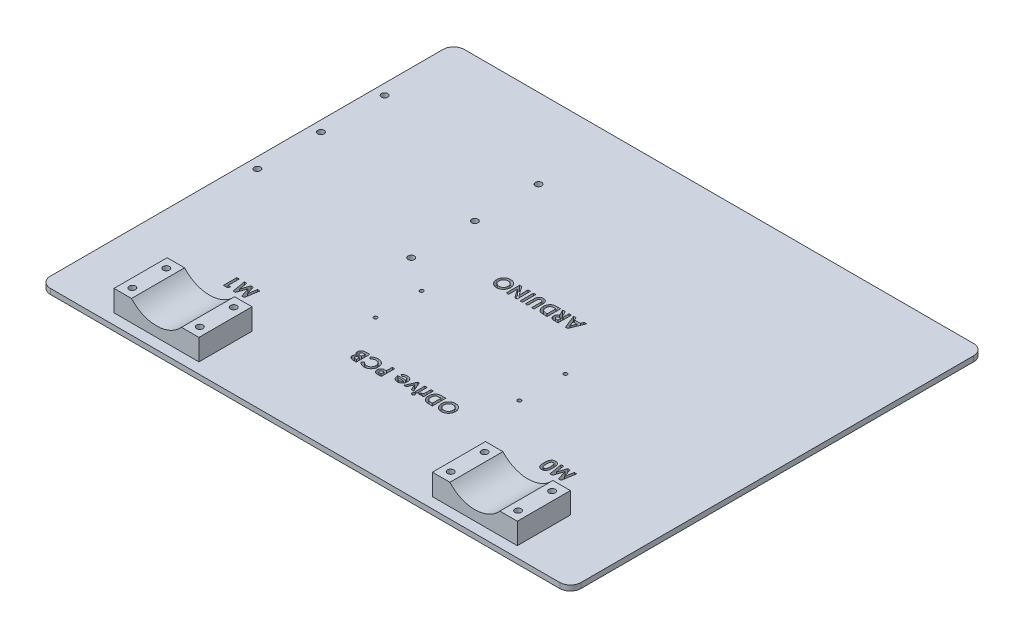
SolidWorks part; units mm, degrees
ref_plane "Plan de face" through (0, 0, 0) normal (0, 0, 1) x (1, 0, 0)
ref_plane "Plan de dessus" through (0, 0, 0) normal (0, 1, 0) x (1, 0, 0)
ref_plane "Plan de droite" through (0, 0, 0) normal (1, 0, 0) x (0, 0, -1)
sketch "Esquisse1" plane through (0, 0, 0) normal (0, 1, 0) x (1, 0, 0)
  line L1 (240, -150) -> (-240, -150)
  line L2 (250, -140) -> (250, 140)
  line L3 (240, 150) -> (-240, 150)
  line L4 (-250, -140) -> (-250, 140)
  line L5 (250, -150) -> (-250, 150) construction
  line L6 (250, 150) -> (-250, -150) construction
  arc A0 (-240, -150) -> (-250, -140) centre (-240, -140) cw
  arc A1 (240, -150) -> (250, -140) centre (240, -140) ccw
  arc A2 (250, 140) -> (240, 150) centre (240, 140) ccw
  arc A3 (-240, 150) -> (-250, 140) centre (-240, 140) ccw
  point P0 (0, 0)
  dimension "D3" = 10
  dimension "D1" = 300
  dimension "D2" = 500
extrude "Boss.-Extru.1" add sketch "Esquisse1" along normal blind 5
sketch "Esquisse2" plane through (0, 5, 0) normal (0, 1, 0) x (1, 0, 0)
  line L0 (240, 150) -> (-240, 150) construction
  line L1 (-240, -150) -> (240, -150) construction
  line L2 (250, -140) -> (250, 140) construction
  line L3 (-250, 140) -> (-250, -140) construction
  spline S4 degree 3 poles (74.2, -20.6163) (74.2, -17.2163) (70.8, -17.2163) (70.8, -20.6163) (70.8, -24.0163) (74.2, -24.0163) (74.2, -20.6163) (74.2, -17.2163) (70.8, -17.2163) knots -0.5 0 0 0 0.5 0.5 0.5 1 1 1 1.5 1.5 1.5 weights 1 0.333333 0.333333 1 0.333333 0.333333 1 0.333333 0.333333 only from (74.2, -20.6163) to (74.2, -20.6163)
  spline S5 degree 3 poles (74.2, 22.8837) (74.2, 26.2837) (70.8, 26.2837) (70.8, 22.8837) (70.8, 19.4837) (74.2, 19.4837) (74.2, 22.8837) (74.2, 26.2837) (70.8, 26.2837) knots -0.5 0 0 0 0.5 0.5 0.5 1 1 1 1.5 1.5 1.5 weights 1 0.333333 0.333333 1 0.333333 0.333333 1 0.333333 0.333333 only from (74.2, 22.8837) to (74.2, 22.8837)
  spline S6 degree 3 poles (-61.3, -20.6162) (-61.3, -17.2162) (-64.7, -17.2162) (-64.7, -20.6162) (-64.7, -24.0162) (-61.3, -24.0162) (-61.3, -20.6162) (-61.3, -17.2162) (-64.7, -17.2162) knots -0.5 0 0 0 0.5 0.5 0.5 1 1 1 1.5 1.5 1.5 weights 1 0.333333 0.333333 1 0.333333 0.333333 1 0.333333 0.333333 only from (-61.3, -20.6162) to (-61.3, -20.6162)
  spline S7 degree 3 poles (-61.3, 22.8838) (-61.3, 26.2837) (-64.7, 26.2838) (-64.7, 22.8838) (-64.7, 19.4838) (-61.3, 19.4838) (-61.3, 22.8838) (-61.3, 26.2837) (-64.7, 26.2838) knots -0.5 0 0 0 0.5 0.5 0.5 1 1 1 1.5 1.5 1.5 weights 1 0.333333 0.333333 1 0.333333 0.333333 1 0.333333 0.333333 only from (-61.3, 22.8838) to (-61.3, 22.8838)
  dimension "D1" = 127.1162
  dimension "D2" = 127.1163
  dimension "D3" = 129.3837
  dimension "D4" = 129.3838
  dimension "D5" = 135.5
  dimension "D6" = 175.8
  dimension "D7" = 175.8
  dimension "D8" = 188.7
extrude "Enlèv. mat.-Extru.1" cut sketch "Esquisse2" against normal through all contours S7 | S6 | S5 | S4
sketch "Esquisse3" plane through (0, 0, 150) normal (0, 0, 1) x (1, 0, 0)
  line L0 (-240, 5) -> (240, 5) construction
  line L1 (-190, 5) -> (-110, 5)
  line L2 (-190, 5) -> (-190, 25)
  line L3 (-190, 25) -> (-173.5557, 25)
  line L4 (-110, 5) -> (-110, 25)
  line L5 (-240, 5) -> (-240, 0) construction
  line L6 (-150, -5.8486) -> (-150, 68.1347) construction
  line L7 (-126.4443, 25) -> (-110, 25)
  arc A0 (-173.5557, 25) -> (-126.4443, 25) centre (-150, 45.9136) ccw
  dimension "D4" = 63
  dimension "D1" = 80
  dimension "D2" = 20
  dimension "D3" = 50
  dimension "D5" = 20.9136
  dimension "D6" = 16.4443
extrude "Boss.-Extru.2" add sketch "Esquisse3" along normal blind 50 from offset 60 offset against normal yes
sketch "Esquisse4" plane through (0, 25, 0) normal (0, 1, 0) x (1, 0, 0)
  line L0 (-181.7778, -90) -> (-181.7778, -143.1865) construction
  line L1 (-173.5557, -90) -> (-190, -90) construction
  line L2 (-150, -90) -> (-150, -156.1953) construction
  line L3 (-190, -90) -> (-110, -90) construction
  line L4 (-173.5557, -140) -> (-190, -140) construction
  circle A0 centre (-181.7778, -99) radius 3
  circle A1 centre (-181.7778, -131) radius 3
  circle A2 centre (-118.2222, -131) radius 3
  circle A3 centre (-118.2222, -99) radius 3
  dimension "D1" = 6
  dimension "D2" = 6
  dimension "D4" = 9
  dimension "D3" = 9
extrude "Enlèv. mat.-Extru.2" cut sketch "Esquisse4" against normal through all
mirror "Symétrie1" about plane through (0, 0, 0) normal (1, 0, 0) of "Enlèv. mat.-Extru.2", "Boss.-Extru.2"
sketch "Esquisse5" plane through (0, 5, 0) normal (0, 1, 0) x (1, 0, 0)
  line L0 (250, -140) -> (250, 140) construction
  line L1 (-250, 140) -> (250, 140)
  line L2 (-250, 140) -> (-250, 240)
  line L3 (-250, 240) -> (250, 240)
  line L4 (250, 140) -> (250, 240)
  dimension "D1" = 100
extrude "Boss.-Extru.3" add sketch "Esquisse5" against normal up to surface (5 mm away) up to face at (118.2222, 0, 96)
fillet "Congé1" radius 10 2 edges at (-250, 2.5, -240) (250, 2.5, -240)
sketch "Esquisse6" plane through (0, 5, 0) normal (0, 1, 0) x (1, 0, 0)
  line L0 (-240, 256.0019) -> (-240, 35.9163) construction
  line L1 (-250, 230) -> (-250, -140) construction
  line L2 (240, 240) -> (-240, 240) construction
  circle A0 centre (-240, 165) radius 3
  circle A1 centre (-240, 105) radius 3
  circle A2 centre (-240, 45) radius 3
  circle A6 centre (-95, 165) radius 3
  circle A7 centre (-95, 105) radius 3
  circle A8 centre (-95, 45) radius 3
  dimension "D2" = 6
  dimension "D1" = 10
  dimension "D4" = 75
  dimension "D3" = 3
  dimension "D5" = 2
extrude "Enlèv. mat.-Extru.3" cut sketch "Esquisse6" against normal through all
sketch "Esquisse7" plane through (0, 0, 0) normal (0, -1, 0) x (1, 0, 0)
  line L0 (-250, -230) -> (-250, 140) construction
  line L1 (-237.5, 130) -> (-222.5, 130)
  line L2 (-237.5, 130) -> (-237.5, 115)
  line L3 (-237.5, 115) -> (-222.5, 115)
  line L4 (-222.5, 130) -> (-222.5, 115)
  line L5 (-237.5, 130) -> (-222.5, 115) construction
  line L6 (-237.5, 115) -> (-222.5, 130) construction
  line L7 (-240, 150) -> (240, 150) construction
  line L8 (0, 249.5345) -> (0, -298.3398) construction
  line L10 (-237.5, -212.5) -> (-222.5, -212.5)
  line L11 (-237.5, -212.5) -> (-237.5, -227.5)
  line L12 (-237.5, -227.5) -> (-222.5, -227.5)
  line L13 (-222.5, -212.5) -> (-222.5, -227.5)
  line L14 (-237.5, -212.5) -> (-222.5, -227.5) construction
  line L15 (-237.5, -227.5) -> (-222.5, -212.5) construction
  line L16 (240, -240) -> (-240, -240) construction
  line L17 (237.5, -227.5) -> (222.5, -212.5) construction
  line L18 (237.5, -212.5) -> (222.5, -227.5) construction
  line L19 (237.5, 115) -> (222.5, 130) construction
  line L20 (237.5, 130) -> (222.5, 115) construction
  line L21 (222.5, -212.5) -> (222.5, -227.5)
  line L22 (237.5, -227.5) -> (222.5, -227.5)
  line L23 (237.5, -212.5) -> (237.5, -227.5)
  line L24 (237.5, -212.5) -> (222.5, -212.5)
  line L25 (222.5, 130) -> (222.5, 115)
  line L26 (237.5, 115) -> (222.5, 115)
  line L27 (237.5, 130) -> (237.5, 115)
  line L28 (237.5, 130) -> (222.5, 130)
  point P0 (-230, 122.5)
  point P12 (-230, -220)
  point P28 (230, -220)
  point P29 (230, 122.5)
  dimension "D1" = 15
  dimension "D2" = 20
  dimension "D3" = 20
  dimension "D4" = 15
  dimension "D5" = 15
  dimension "D6" = 20
  dimension "D7" = 20
extrude "Boss.-Extru.4" add sketch "Esquisse7" along normal blind 10
fillet "Congé2" radius 5 32 edges at (222.5, 0, -220) (-230, 0, -212.5) (-230, 0, -227.5) (230, 0, -212.5) (230, 0, -227.5) (230, 0, 115) (-237.5, -5, -227.5) (-237.5, 0, -220) (-237.5, -5, -212.5) (-222.5, -5, -212.5) (-222.5, -5, -227.5) (-222.5, 0, -220) (237.5, -5, -212.5) (222.5, -5, -212.5) (222.5, -5, -227.5) (237.5, -5, -227.5) (237.5, 0, -220) (237.5, -5, 130) (237.5, -5, 115) (237.5, 0, 122.5) (230, 0, 130) (222.5, 0, 122.5) (222.5, -5, 115) (222.5, -5, 130) (-222.5, -5, 130) (-237.5, -5, 130) (-237.5, -5, 115) (-222.5, -5, 115) (-222.5, 0, 122.5) (-230, 0, 115) (-230, 0, 130) (-237.5, 0, 122.5)
sketch "Esquisse8" plane through (0, 5, 0) normal (0, 1, 0) x (1, 0, 0)
  line L0 (184.1896, -53.3453) -> (109.3581, -53.3453) construction
  line L1 (-112.9445, -53.3453) -> (-190.483, -53.3453) construction
  line L2 (73.0317, -53.3453) -> (-66.49, -53.3453) construction
  line L3 (68.9359, 73.7462) -> (-66.49, 73.7462) construction
  text T0 "<b>M0</b>" font "Century Gothic" height in points 48
  text T1 "<b>M1</b>" font "Century Gothic" height in points 48
  text T2 "<b>ODrive PCB</b>" font "Century Gothic" height in points 48
  text T3 "<b>ARDUINO</b>" font "Century Gothic" height in points 48
extrude "Enlèv. mat.-Extru.4" cut sketch "Esquisse8" against normal through all
